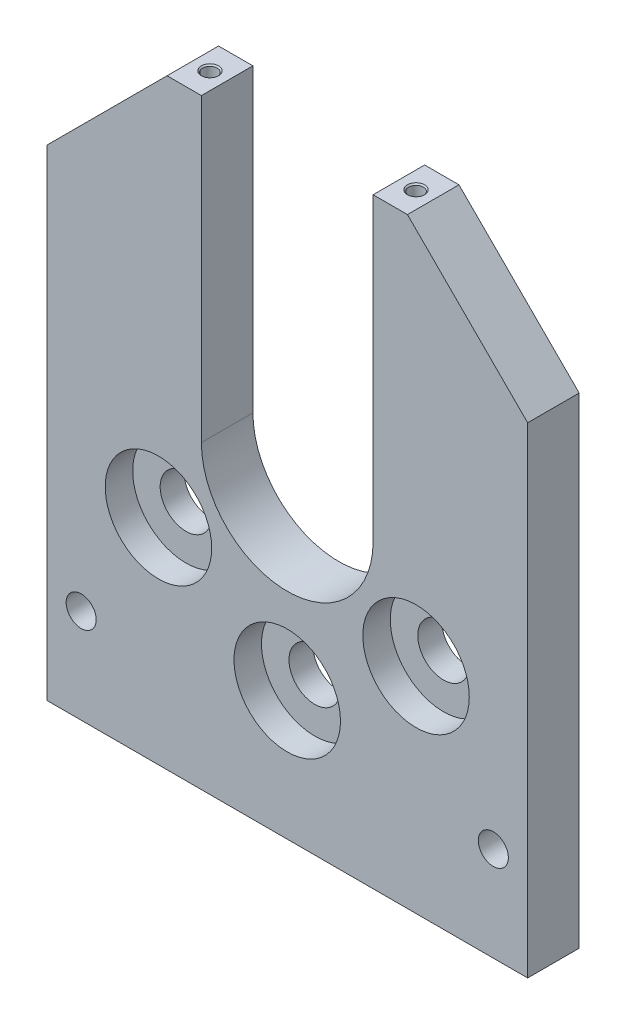
SolidWorks part; units mm, degrees
ref_plane "Front Plane" through (0, 0, 0) normal (0, 0, 1) x (1, 0, 0)
ref_plane "Top Plane" through (0, 0, 0) normal (0, 1, 0) x (1, 0, 0)
ref_plane "Right Plane" through (0, 0, 0) normal (1, 0, 0) x (0, 0, -1)
sketch "Sketch1" plane through (0, 0, 0) normal (0, 1, 0) x (1, 0, 0)
  line L1 (-140, 15) -> (140, 15)
  line L2 (-140, 15) -> (-140, -15)
  line L3 (-140, -15) -> (140, -15)
  line L4 (140, 15) -> (140, -15)
  line L5 (-140, 15) -> (140, -15) construction
  line L6 (-140, -15) -> (140, 15) construction
  point P0 (0, 0)
  dimension "D1" = 280
  dimension "D2" = 30
extrude "Boss-Extrude1" add sketch "Sketch1" along normal blind 350
sketch "Sketch2" plane through (0, 0, 15) normal (0, 0, 1) x (1, 0, 0)
  line L0 (0, 350) -> (0, 175) construction
  line L1 (-140, 350) -> (140, 350) construction
  line L2 (50, 350) -> (50, 175)
  line L3 (-50, 350) -> (-50, 175)
  arc A0 (50, 350) -> (-50, 350) centre (0, 350) ccw
  arc A1 (-50, 175) -> (50, 175) centre (0, 175) ccw
  point P5 (0, 262.5)
  point P10 (0, 125)
  dimension "D1" = 100
  dimension "D2" = 225
extrude "Cut-Extrude1" cut sketch "Sketch2" against normal blind 350
chamfer "Chamfer1" distance 70 angle 45 2 edges at (-140, 350, 0) (140, 350, 0)
sketch "Sketch8" plane through (0, 350, 0) normal (0, 1, 0) x (1, 0, 0)
  point P0 (-60, 0)
  point P1 (60, 0)
  dimension "D1" = 60
  dimension "D2" = 60
hole_wizard "M10 Tapped Hole3" positions "3DSketch4" profile "Sketch10" tap size "M10" standard "ISO"
sketch3d "3DSketch4"
  point P0 (-60, 350, 0)
  point P3 (60, 350, 0)
sketch "Sketch10" plane through (-60, 350, 0) normal (1, 0, 0) x (0, 0, 1)
  line L0 (0, 0) -> (0, 27.0537)
  line L1 (0, 27.0537) -> (4.25, 24.5)
  line L2 (4.25, 24.5) -> (4.25, 0.775)
  line L3 (4.25, 0.775) -> (5.025, 0)
  line L5 (5.025, 0) -> (0, 0)
  line L6 (-4.25, 0.775) -> (-5.025, 0) construction
  line L10 (0, 27.0537) -> (-4.25, 24.5) construction
  line L11 (0, -6.35) -> (0, 107.95) construction
  dimension "Tap Drill Dia." = 8.5
  dimension "Tap Drill Depth" = 24.5
  dimension "Near C'Sink Dia." = 10.05
  dimension "Near C'Sink Angle" = 90
  dimension "Drill Angle" = 118
cosmetic thread "Hole Thread5" parameters "D1"=20, "D2"=10
cosmetic thread "Hole Thread6" parameters "D1"=20, "D2"=10
sketch "Sketch11" plane through (0, 0, 15) normal (0, 0, 1) x (1, 0, 0)
  line L0 (-140, 0) -> (140, 0) construction
  line L1 (-140, 280) -> (-140, 0) construction
  line L2 (140, 280) -> (140, 0) construction
  circle A0 centre (-120, 55) radius 8.75
  circle A1 centre (120, 55) radius 8.75
  dimension "D1" = 17.5
  dimension "D4" = 20
  dimension "D2" = 55
  dimension "D3" = 20
  dimension "D5" = 55
extrude "Cut-Extrude3" cut sketch "Sketch11" against normal blind 350
sketch "Sketch12" plane through (0, 0, 15) normal (0, 0, 1) x (1, 0, 0)
  circle A0 centre (-75, 124.7494) radius 15
  circle A1 centre (75, 124.7494) radius 15
  circle A2 centre (0, 75) radius 15
  arc A3 (-50, 175) -> (50, 175) centre (0, 175) ccw construction
  point P11 (0, 125)
  dimension "D1" = 30
  dimension "D2" = 90
  dimension "D3" = 90
  dimension "D4" = 75
  dimension "D5" = 75
  dimension "D6" = 75
extrude "Cut-Extrude4" cut sketch "Sketch12" against normal blind 350
sketch "Sketch13" plane through (0, 0, 15) normal (0, 0, 1) x (1, 0, 0)
  circle A0 centre (-75, 124.7494) radius 31
  circle A1 centre (0, 75) radius 31
  circle A2 centre (75, 124.7494) radius 31
  dimension "D1" = 62
extrude "Cut-Extrude5" cut sketch "Sketch13" against normal blind 16
